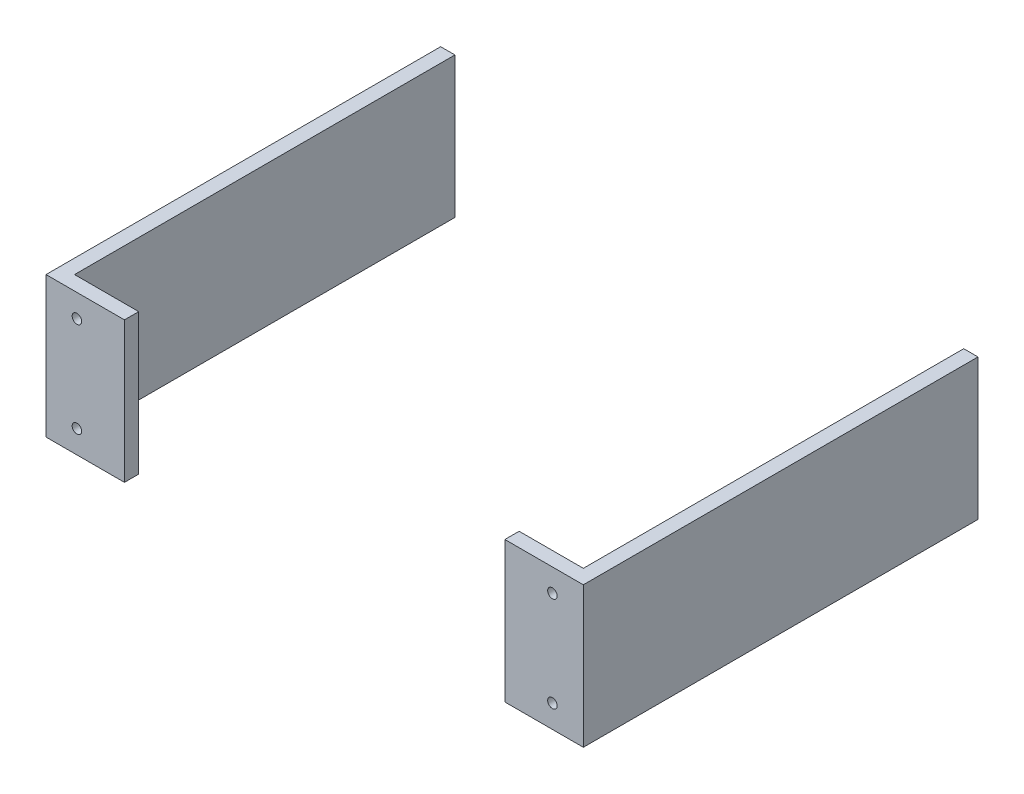
SolidWorks part; units mm, degrees
ref_plane "Front Plane" through (0, 0, 0) normal (0, 0, 1) x (1, 0, 0)
ref_plane "Top Plane" through (0, 0, 0) normal (0, 1, 0) x (1, 0, 0)
ref_plane "Right Plane" through (0, 0, 0) normal (1, 0, 0) x (0, 0, -1)
sketch "Sketch1" plane through (0, 0, 0) normal (0, 0, 1) x (1, 0, 0)
  line L1 (56.5, -15) -> (-56.5, -15)
  line L2 (56.5, -15) -> (56.5, 15)
  line L3 (56.5, 15) -> (-56.5, 15)
  line L4 (-56.5, -15) -> (-56.5, 15)
  line L5 (56.5, -15) -> (-56.5, 15) construction
  line L6 (56.5, 15) -> (-56.5, -15) construction
  point P0 (0, 0)
  dimension "D1" = 30
  dimension "D2" = 113
extrude "Boss-Extrude1" add sketch "Sketch1" along normal blind 3
sketch "Sketch2" plane through (0, 0, 0) normal (0, 0, -1) x (-1, 0, 0)
  line L0 (56.5, -15) -> (-56.5, -15) construction
  line L1 (-56.5, 15) -> (-53.5, 15)
  line L2 (-56.5, 15) -> (-56.5, -15)
  line L3 (-56.5, -15) -> (-53.5, -15)
  line L4 (-53.5, 15) -> (-53.5, -15)
  line L6 (56.5, 15) -> (53.5, 15)
  line L7 (56.5, 15) -> (56.5, -15)
  line L8 (56.5, -15) -> (53.5, -15)
  line L9 (53.5, 15) -> (53.5, -15)
  dimension "D1" = 3
  dimension "D2" = 3
extrude "Boss-Extrude2" add sketch "Sketch2" along normal blind 80
sketch "Sketch3" plane through (0, 0, 3) normal (0, 0, 1) x (1, 0, 0)
  line L1 (50, -10) -> (-50, -10) construction
  line L2 (50, -10) -> (50, 10) construction
  line L3 (50, 10) -> (-50, 10) construction
  line L4 (-50, -10) -> (-50, 10) construction
  line L5 (50, -10) -> (-50, 10) construction
  line L6 (50, 10) -> (-50, -10) construction
  point P0 (0, 0)
  dimension "D1" = 100
  dimension "D2" = 20
sketch "Sketch4" plane through (0, 0, 3) normal (0, 0, 1) x (1, 0, 0)
  circle A0 centre (-50, 10) radius 1
  circle A1 centre (50, 10) radius 1
  circle A2 centre (50, -10) radius 1
  circle A3 centre (-50, -10) radius 1
extrude "Cut-Extrude1" cut sketch "Sketch4" against normal blind 10.5
sketch "Sketch5" plane through (0, 0, 3) normal (0, 0, 1) x (1, 0, 0)
  line L0 (56.5, 15) -> (-56.5, 15) construction
  line L1 (40, -15) -> (-40, -15)
  line L2 (40, -15) -> (40, 15)
  line L3 (40, 15) -> (-40, 15)
  line L4 (-40, -15) -> (-40, 15)
  line L5 (40, -15) -> (-40, 15) construction
  line L6 (40, 15) -> (-40, -15) construction
  point P0 (0, 0)
  dimension "D1" = 80
extrude "Cut-Extrude2" cut sketch "Sketch5" against normal through all
sketch "Sketch6" plane through (0, 15, 0) normal (0, 1, 0) x (1, 0, 0)
  line L1 (62.5934, -83.736) -> (-62.5934, -83.736)
  line L2 (62.5934, -83.736) -> (62.5934, 83.736)
  line L3 (62.5934, 83.736) -> (-62.5934, 83.736)
  line L4 (-62.5934, -83.736) -> (-62.5934, 83.736)
  line L5 (62.5934, -83.736) -> (-62.5934, 83.736) construction
  line L6 (62.5934, 83.736) -> (-62.5934, -83.736) construction
  point P0 (0, 0)
extrude "Cut-Extrude3" cut sketch "Sketch6" against normal blind 0.2
sketch "Sketch7" plane through (0, -15, 0) normal (0, -1, 0) x (1, 0, 0)
  line L1 (-68.6006, 88.4123) -> (68.6006, 88.4123)
  line L2 (-68.6006, 88.4123) -> (-68.6006, -88.4123)
  line L3 (-68.6006, -88.4123) -> (68.6006, -88.4123)
  line L4 (68.6006, 88.4123) -> (68.6006, -88.4123)
  line L5 (-68.6006, 88.4123) -> (68.6006, -88.4123) construction
  line L6 (-68.6006, -88.4123) -> (68.6006, 88.4123) construction
  point P0 (0, 0)
extrude "Cut-Extrude4" cut sketch "Sketch7" against normal blind 0.2
